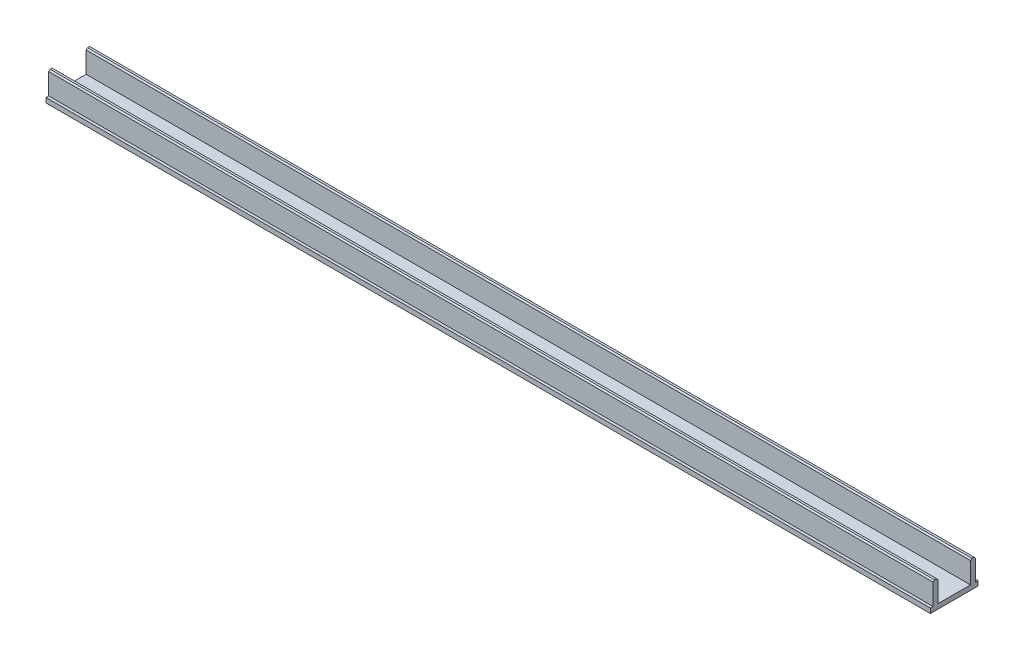
SolidWorks part; units mm, degrees
material "ABS"
ref_plane "Front" through (0, 0, 0) normal (0, 0, 1) x (1, 0, 0)
ref_plane "Top" through (0, 0, 0) normal (0, 1, 0) x (1, 0, 0)
ref_plane "Right" through (0, 0, 0) normal (1, 0, 0) x (0, 0, -1)
sketch "草图1" plane through (0, 0, 0) normal (1, 0, 0) x (0, 0, -1)
  line L0 (2.4, 4) -> (3.1, 4)
  line L1 (-3.1, 4) -> (-2.4, 4)
  line L2 (-3.5, 0.7) -> (-3.5, 0)
  line L3 (-3.5, 0) -> (3.5, 0)
  line L4 (3.5, 0.7) -> (3.5, 0)
  line L6 (-2.4, 4) -> (-2.4, 0.7)
  line L7 (-2.4, 0.7) -> (2.4, 0.7)
  line L8 (2.4, 4) -> (2.4, 0.7)
  line L12 (-3.5, 0.7) -> (-3.1, 0.7)
  line L13 (-3.1, 4) -> (-3.1, 0.7)
  line L16 (3.5, 0.7) -> (3.1, 0.7)
  line L17 (3.1, 4) -> (3.1, 0.7)
  dimension "D1" = 7
  dimension "D2" = 0.7
  dimension "D3" = 0.7
  dimension "D4" = 0.4
  dimension "D5" = 0.7
  dimension "D6" = 0.4
  dimension "D7" = 4
extrude "凸台-拉伸1" add sketch "草图1" along normal blind 130
chamfer "倒角1" distance 0.2 angle 45 4 edges at (65, 4, -3.1) (65, 4, -2.4) (65, 4, 2.4) (65, 4, 3.1)
